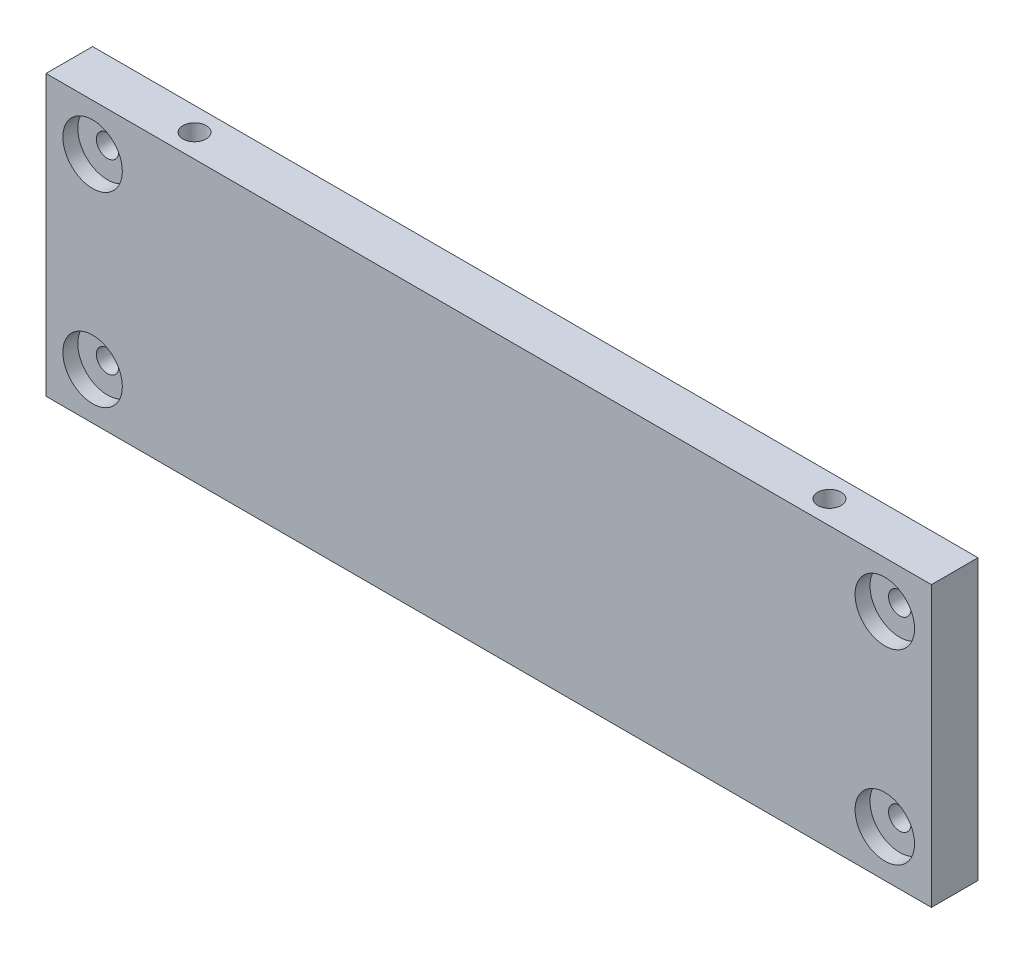
SolidWorks part; units mm, degrees
ref_plane "Front Plane" through (0, 0, 0) normal (0, 0, 1) x (1, 0, 0)
ref_plane "Top Plane" through (0, 0, 0) normal (0, 1, 0) x (1, 0, 0)
ref_plane "Right Plane" through (0, 0, 0) normal (1, 0, 0) x (0, 0, -1)
sketch "Sketch1" plane through (0, 0, 0) normal (0, 0, 1) x (1, 0, 0)
  line L1 (47.5, -15) -> (-47.5, -15)
  line L2 (47.5, -15) -> (47.5, 15)
  line L3 (47.5, 15) -> (-47.5, 15)
  line L4 (-47.5, -15) -> (-47.5, 15)
  line L5 (0, 15) -> (0, -15) construction
  line L6 (47.5, 0) -> (-47.5, 0) construction
  point P0 (0, 0)
  dimension "D1" = 95
  dimension "D2" = 30
extrude "Boss-Extrude1" add sketch "Sketch1" along normal blind 5
sketch "Sketch2" plane through (0, 0, 5) normal (0, 0, 1) x (1, 0, 0)
  line L12 (-42.5, 10) -> (-42.5, -10)
  line L13 (-42.5, -10) -> (42.5, -10)
  line L14 (42.5, -10) -> (42.5, 10)
  line L15 (42.5, 10) -> (-42.5, 10)
  line L36 (-47.5, 15) -> (-47.5, -15) construction
  line L38 (47.5, -15) -> (47.5, 15) construction
  line L39 (47.5, 15) -> (-47.5, 15) construction
  line L40 (-47.5, -15) -> (47.5, -15) construction
  point P1 (-42.5, 10)
  point P2 (-42.5, -10)
  point P3 (42.5, -10)
  point P4 (42.5, 10)
  dimension "D1" = 5
  dimension "D2" = 5
  dimension "D3" = 5
  dimension "D4" = 5
hole_wizard "CBORE for M2 Hex Head Machine Screw1" positions "Sketch2" profile "Sketch3" counterbore size "M2" standard "ANSI Metric" end condition through all
sketch "Sketch3" plane through (-42.5, 10, 5) normal (1, 0, 0) x (0, -1, 0)
  line L0 (0, 0) -> (0, 5)
  line L1 (0, 5) -> (1.2, 5)
  line L3 (1.2, 5) -> (1.2, 1.6)
  line L4 (1.2, 1.6) -> (3.19, 1.6)
  line L5 (3.19, 1.6) -> (3.19, 0)
  line L7 (3.19, 0) -> (0, 0)
  line L11 (0, -6.35) -> (0, 107.95) construction
  dimension "Thru Hole Dia." = 2.4
  dimension "Thru Hole Depth" = 5
  dimension "C'Bore Dia." = 6.38
  dimension "C'Bore Depth" = 1.6
sketch "Sketch4" plane through (0, 15, 0) normal (0, 1, 0) x (1, 0, 0)
  line L1 (0, -2.5) -> (0, 25.0792) construction
  line L2 (47.5, -2.5) -> (-47.5, -2.5)
  line L3 (47.5, -2.5) -> (-47.5, -2.5)
  point P1 (-34.0619, -2.5)
  point P3 (34.0619, -2.5)
  dimension "D1" = 2.5
hole_wizard "M3x0.5 Tapped Hole1" positions "Sketch4" profile "Sketch5" tap size "M3x0.5" standard "ANSI Metric"
cosmetic thread "Hole Thread9" parameters "D1"=25, "D2"=3
cosmetic thread "Hole Thread10" parameters "D1"=25, "D2"=3
sketch "Sketch5" plane through (34.0619, 15, 2.5) normal (1, 0, 0) x (0, 0, 1)
  line L0 (0, 0) -> (0, 3.7511)
  line L1 (0, 3.7511) -> (1.25, 3)
  line L2 (1.25, 3) -> (1.25, 0)
  line L5 (1.25, 0) -> (0, 0)
  line L10 (0, 3.7511) -> (-1.25, 3) construction
  line L11 (0, -6.35) -> (0, 107.95) construction
  dimension "Tap Drill Dia." = 2.5
  dimension "Tap Drill Depth" = 3
  dimension "Drill Angle" = 118
